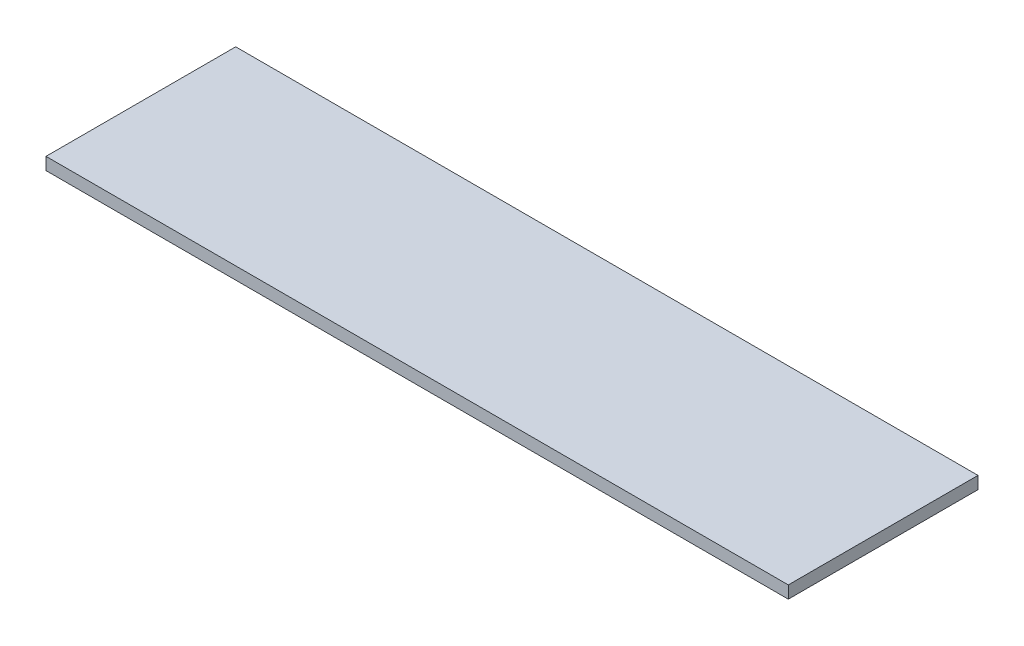
SolidWorks part; units mm, degrees
ref_plane "正面" through (0, 0, 0) normal (0, 0, 1) x (1, 0, 0)
ref_plane "平面" through (0, 0, 0) normal (0, 1, 0) x (1, 0, 0)
ref_plane "右側面" through (0, 0, 0) normal (1, 0, 0) x (0, 0, -1)
sketch "ｽｹｯﾁ1" plane through (0, 0, 0) normal (0, 1, 0) x (1, 0, 0)
  line L1 (-80, 23) -> (100, 23)
  line L2 (-80, 23) -> (-80, -23)
  line L3 (-80, -23) -> (100, -23)
  line L4 (100, 23) -> (100, -23)
  dimension "D1" = 46
  dimension "D2" = 23
  dimension "D3" = 180
  dimension "D4" = 80
extrude "ﾎﾞｽ - 押し出し1" add sketch "ｽｹｯﾁ1" along normal mid plane 3
